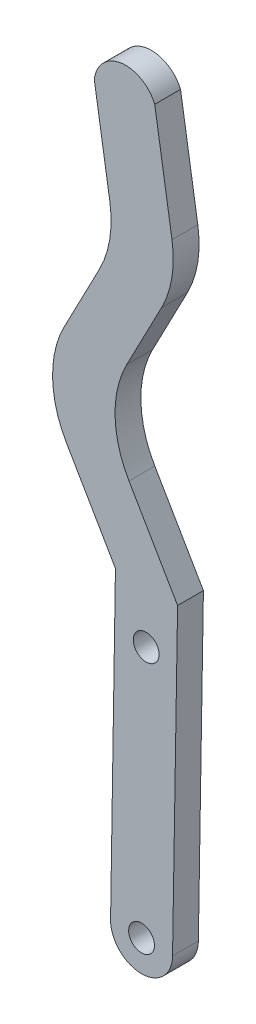
SolidWorks part; units mm, degrees
ref_plane "Спереди" through (0, 0, 0) normal (0, 0, 1) x (1, 0, 0)
ref_plane "Сверху" through (0, 0, 0) normal (0, 1, 0) x (1, 0, 0)
ref_plane "Справа" through (0, 0, 0) normal (1, 0, 0) x (0, 0, -1)
sketch "Эскиз1" plane through (0, 0, 0) normal (0, 0, 1) x (1, 0, 0)
  line L0 (-5.9968, 0.1966) -> (-5.057, 59.4439)
  line L1 (6, 0) -> (6.9768, 59.2455)
  line L3 (-5.057, 59.4439) -> (-14.5202, 75.7155)
  line L4 (6.9768, 59.2455) -> (-2.4273, 75.4156)
  line L5 (-14.963, 95.0217) -> (-8.1607, 108.0591)
  line L6 (-2.8702, 94.7218) -> (3.8751, 107.6499)
  line L7 (5.8952, 120.0428) -> (2.5499, 141.0762)
  line L8 (-6.1406, 120.452) -> (-9.1574, 139.4202)
  circle A0 centre (0, 0) radius 2.5
  arc A1 (-5.9968, 0.1966) -> (6, 0) centre (0, 0) ccw
  circle A2 centre (0.8961, 49.2222) radius 2.5
  arc A3 (-9.1574, 139.4202) -> (2.5499, 141.0762) centre (-3.0843, 138.6972) cw
  arc A4 (-14.963, 95.0217) -> (-14.5202, 75.7155) centre (2.7686, 85.7702) ccw
  arc A5 (-2.4273, 75.4156) -> (-2.8702, 94.7218) centre (14.8615, 85.4703) cw
  arc A6 (-8.1607, 108.0591) -> (-6.1406, 120.452) centre (-25.8923, 117.3106) ccw
  arc A7 (3.8751, 107.6499) -> (5.8952, 120.0428) centre (-13.8566, 116.9014) ccw
  dimension "D1" = 20
extrude "Вытянуть1" add sketch "Эскиз1" along normal blind 5
